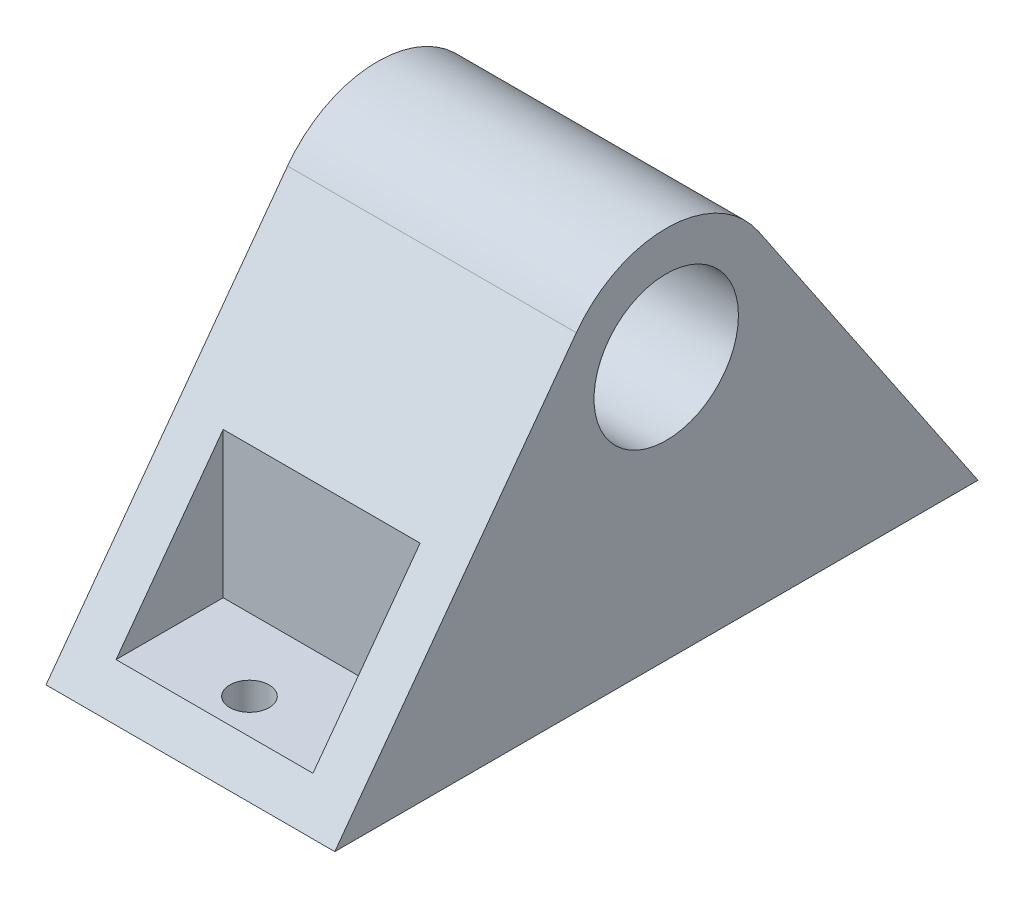
SolidWorks part; units mm, degrees
ref_plane "Plano frontal" through (0, 0, 0) normal (0, 0, 1) x (1, 0, 0)
ref_plane "Plano superior" through (0, 0, 0) normal (0, 1, 0) x (1, 0, 0)
ref_plane "Plano direito" through (0, 0, 0) normal (1, 0, 0) x (0, 0, -1)
sketch "Esboço1" plane through (0, 0, 0) normal (1, 0, 0) x (0, 0, -1)
  line L0 (-6.0989, 25.0342) -> (-24.5, 0)
  line L1 (-24.5, 0) -> (24.5, 0)
  line L2 (7.7959, 24.7545) -> (24.5, 0)
  circle A2 centre (0.75, 20) radius 8.5
  circle A3 centre (0.75, 20) radius 5.5
  dimension "D1" = 17
  dimension "D2" = 11
  dimension "D3" = 0.75
  dimension "D4" = 49
  dimension "D5" = 20
  dimension "D6" = 126.317
extrude "Ressalto-extrusão1" add sketch "Esboço1" along normal blind 22
ref_plane "Plano1" through (0, 28.5, 0) normal (0, 1, 0) x (1, 0, 0)
sketch "Esboço5" plane through (0, 28.5, 0) normal (0, 1, 0) x (1, 0, 0)
  line L0 (22, 24.5) -> (0, 24.5) construction
  line L1 (3.5, 24.5) -> (18.5, 24.5)
  line L2 (3.5, 24.5) -> (3.5, 14.5)
  line L3 (3.5, 14.5) -> (18.5, 14.5)
  line L4 (18.5, 24.5) -> (18.5, 14.5)
  line L5 (22, -24.5) -> (0, -24.5) construction
  line L7 (3.5, -24.5) -> (18.5, -24.5)
  line L8 (3.5, -24.5) -> (3.5, -14.5)
  line L9 (3.5, -14.5) -> (18.5, -14.5)
  line L10 (18.5, -24.5) -> (18.5, -14.5)
  point P6 (11, 14.5)
  dimension "D1" = 15
  dimension "D2" = 10
  dimension "D3" = 11
extrude "Corte-extrusão3" cut sketch "Esboço5" against normal blind 26
sketch "Esboço6" plane through (0, 28.5, 0) normal (0, 1, 0) x (1, 0, 0)
  line L0 (22, 7.7959) -> (22, 24.5) construction
  line L1 (22, -24.5) -> (0, -24.5) construction
  circle A0 centre (11, 20) radius 1.5
  circle A1 centre (11, -20) radius 1.5
  dimension "D1" = 3
  dimension "D2" = 11
  dimension "D3" = 40
  dimension "D4" = 4.5
extrude "Corte-extrusão4" cut sketch "Esboço6" against normal through all
